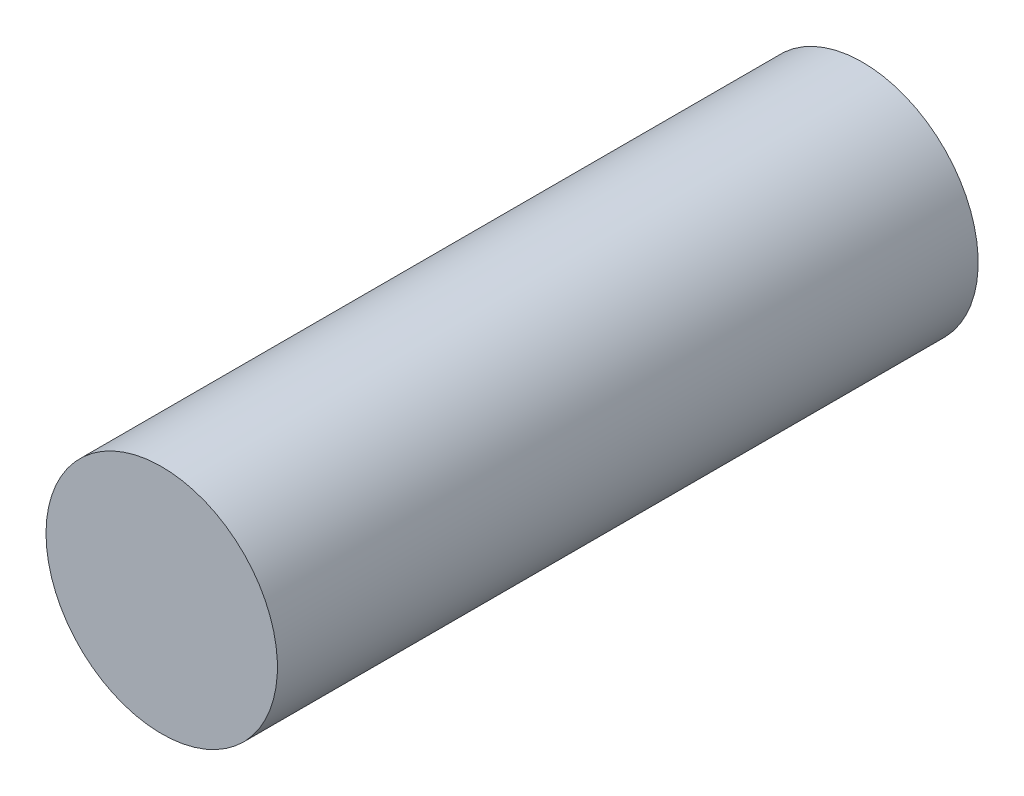
SolidWorks part; units mm, degrees
ref_plane "Alzado" through (0, 0, 0) normal (0, 0, 1) x (1, 0, 0)
ref_plane "Planta" through (0, 0, 0) normal (0, 1, 0) x (1, 0, 0)
ref_plane "Vista lateral" through (0, 0, 0) normal (1, 0, 0) x (0, 0, -1)
sketch "Croquis1" plane through (0, 0, 0) normal (0, 0, 1) x (1, 0, 0)
  circle A0 centre (0, 0) radius 7.15
  dimension "D1" = 14.3
extrude "Saliente-Extruir1" add sketch "Croquis1" along normal blind 43.3
